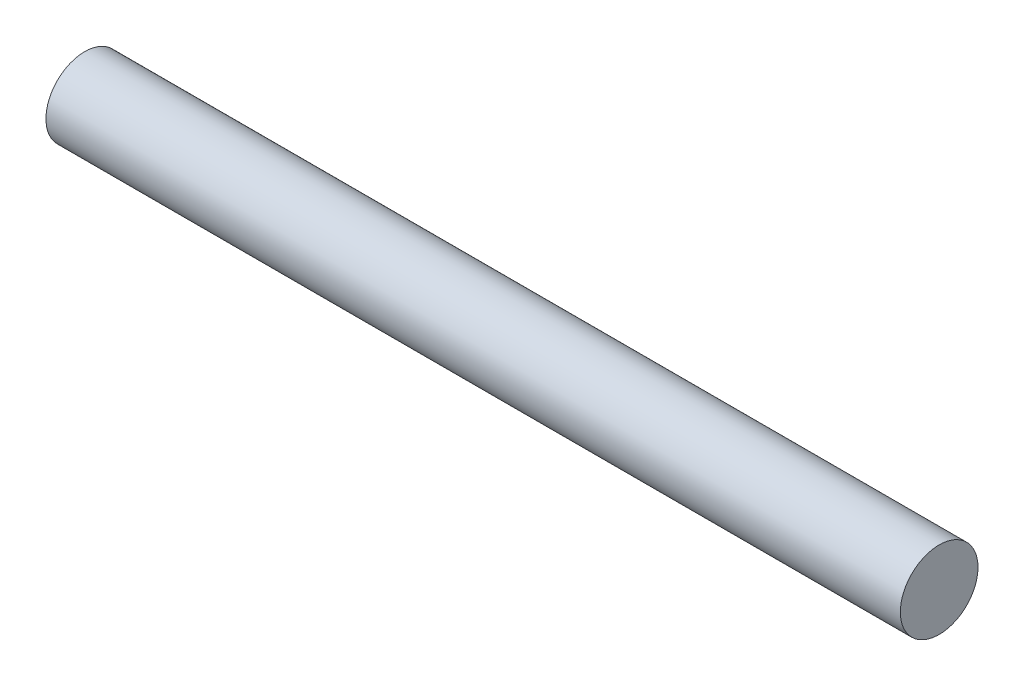
SolidWorks part; units mm, degrees
material "Cast Alloy Steel"
ref_plane "Front Plane" through (0, 0, 0) normal (0, 0, 1) x (1, 0, 0)
ref_plane "Top Plane" through (0, 0, 0) normal (0, 1, 0) x (1, 0, 0)
ref_plane "Right Plane" through (0, 0, 0) normal (1, 0, 0) x (0, 0, -1)
sketch "Sketch2" plane through (0, 0, 0) normal (1, 0, 0) x (0, 0, -1)
  circle A0 centre (0, 0) radius 2.54
extrude "Boss-Extrude1" add sketch "Sketch2" along normal blind 55.88
